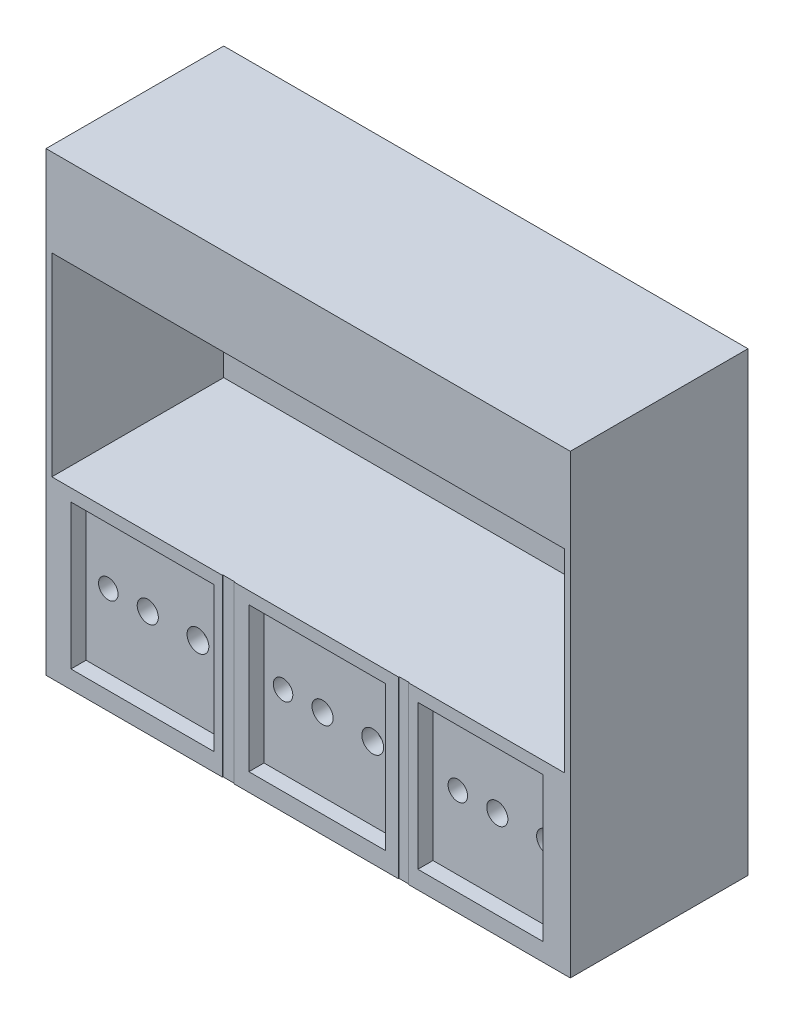
SolidWorks part; units mm, degrees
ref_plane "Alzado" through (0, 0, 0) normal (0, 0, 1) x (1, 0, 0)
ref_plane "Planta" through (0, 0, 0) normal (0, 1, 0) x (1, 0, 0)
ref_plane "Vista lateral" through (0, 0, 0) normal (1, 0, 0) x (0, 0, -1)
sketch "Croquis1" plane through (0, 0, 0) normal (0, 1, 0) x (1, 0, 0)
  line L1 (-900, 305) -> (900, 305)
  line L2 (-900, 305) -> (-900, -305)
  line L3 (-900, -305) -> (900, -305)
  line L4 (900, 305) -> (900, -305)
  line L5 (-900, 305) -> (900, -305) construction
  line L6 (-900, -305) -> (900, 305) construction
  point P0 (0, 0)
  dimension "D1" = 1800
  dimension "D2" = 610
extrude "Saliente-Extruir1" add sketch "Croquis1" along normal blind 600
sketch "Croquis2" plane through (0, 0, 305) normal (0, 0, 1) x (1, 0, 0)
  line L0 (-900, 0) -> (900, 0) construction
  line L2 (-294.6483, 600) -> (-253.9268, 600)
  line L4 (-294.6483, 600) -> (-294.6483, 0)
  line L5 (-294.6483, 0) -> (-253.9268, 0)
  line L6 (-253.9268, 600) -> (-253.9268, 0)
  line L7 (-294.6483, 600) -> (-253.9268, 0) construction
  line L8 (-294.6483, 0) -> (-253.9268, 600) construction
  line L9 (-900, 600) -> (900, 600) construction
  line L11 (310.3007, 600) -> (344.9141, 600)
  line L12 (310.3007, 600) -> (310.3007, 0)
  line L13 (310.3007, 0) -> (344.9141, 0)
  line L14 (344.9141, 600) -> (344.9141, 0)
  line L15 (310.3007, 600) -> (344.9141, 0) construction
  line L16 (310.3007, 0) -> (344.9141, 600) construction
  point P0 (-274.2876, 300)
  point P8 (327.6074, 300)
extrude "Cortar-Extruir1" cut sketch "Croquis2" against normal blind 2
sketch "Croquis3" plane through (0, 0, 305) normal (0, 0, 1) x (1, 0, 0)
  line L1 (-814.4269, 557.9948) -> (-323.5395, 557.9948)
  line L2 (-814.4269, 557.9948) -> (-814.4269, 61.5291)
  line L3 (-814.4269, 61.5291) -> (-323.5395, 61.5291)
  line L4 (-323.5395, 557.9948) -> (-323.5395, 61.5291)
  line L5 (-814.4269, 557.9948) -> (-323.5395, 61.5291) construction
  line L6 (-814.4269, 61.5291) -> (-323.5395, 557.9948) construction
  line L7 (-203.6067, 557.9948) -> (264.9677, 557.9948)
  line L8 (-203.6067, 557.9948) -> (-203.6067, 61.5291)
  line L9 (-203.6067, 61.5291) -> (264.9677, 61.5291)
  line L10 (264.9677, 557.9948) -> (264.9677, 61.5291)
  line L11 (-203.6067, 557.9948) -> (264.9677, 61.5291) construction
  line L12 (-203.6067, 61.5291) -> (264.9677, 557.9948) construction
  line L13 (376.533, 557.9948) -> (806.0595, 557.9948)
  line L14 (376.533, 557.9948) -> (376.533, 61.5291)
  line L15 (376.533, 61.5291) -> (806.0595, 61.5291)
  line L16 (806.0595, 557.9948) -> (806.0595, 61.5291)
  line L17 (376.533, 557.9948) -> (806.0595, 61.5291) construction
  line L18 (376.533, 61.5291) -> (806.0595, 557.9948) construction
  point P0 (-568.9832, 309.762)
  point P5 (30.6805, 309.762)
  point P10 (591.2963, 309.762)
extrude "Cortar-Extruir2" cut sketch "Croquis3" against normal blind 52
sketch "Croquis4" plane through (0, 0, 253) normal (0, 0, 1) x (1, 0, 0)
  circle A0 centre (-738.2, 312.5511) radius 33.4696
  circle A1 centre (-602.6428, 312.5511) radius 36.2587
  circle A2 centre (-430.4054, 312.5511) radius 37.4202
extrude "Cortar-Extruir3" cut sketch "Croquis4" against normal blind 52
pattern_linear "MatrizL1" count 3 spacing 600 along (1, 0, 0) of "Cortar-Extruir3"
sketch "Croquis5" plane through (0, 600, 0) normal (0, 1, 0) x (1, 0, 0)
  line L0 (900, -305) -> (880, -305)
  line L1 (-900, -305) -> (-900, 305)
  line L2 (-900, 305) -> (900, 305)
  line L3 (900, 305) -> (900, -305)
  line L4 (880, 285) -> (880, -285)
  line L5 (-880, -285) -> (-880, -305)
  line L6 (-880, -285) -> (-880, 285)
  line L7 (-880, 285) -> (880, 285)
  line L9 (880, -285) -> (880, -305)
  line L10 (-880, -305) -> (-900, -305)
  line L11 (880, -285) -> (-880, -285) construction
  line L12 (900, -305) -> (-900, -305) construction
  dimension "D1" = 20
extrude "Saliente-Extruir2" add sketch "Croquis5" along normal blind 666
sketch "Croquis6" plane through (0, 1266, 0) normal (0, 1, 0) x (1, 0, 0)
  line L0 (-900, 305) -> (900, 305)
  line L1 (900, 305) -> (900, -305)
  line L2 (900, -305) -> (-900, -305)
  line L3 (-900, -305) -> (-900, 305)
extrude "Saliente-Extruir3" add sketch "Croquis6" along normal blind 300
